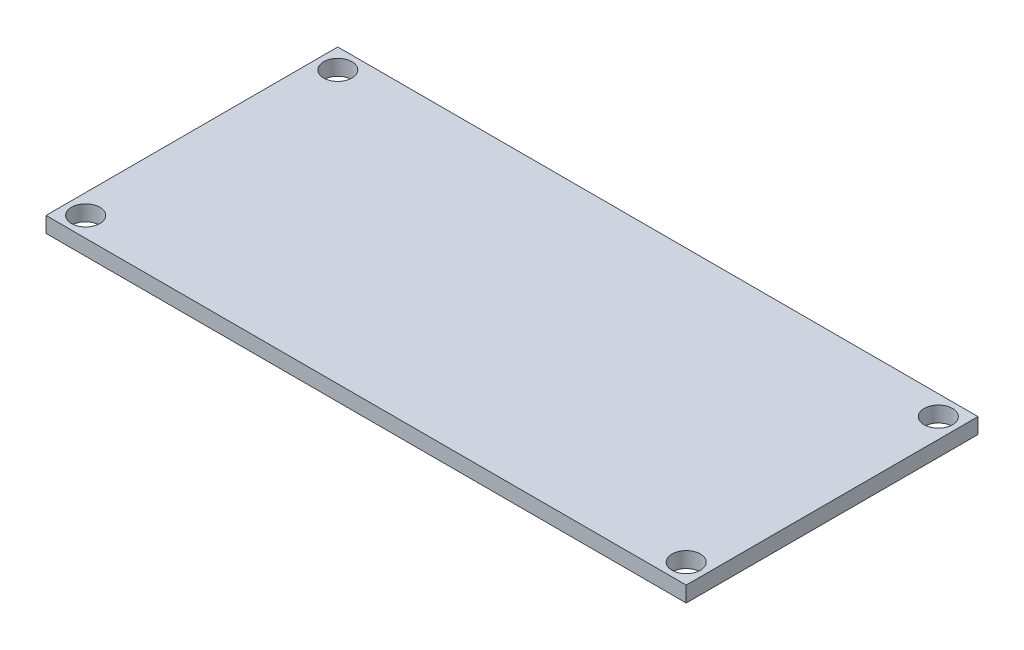
SolidWorks part; units mm, degrees
other "Camera2"
other "Camera3"
other "Camera5"
other "Camera6"
ref_plane "Front Plane" through (0, 0, 0) normal (0, 0, 1) x (1, 0, 0)
ref_plane "Top Plane" through (0, 0, 0) normal (0, 1, 0) x (1, 0, 0)
ref_plane "Right Plane" through (0, 0, 0) normal (1, 0, 0) x (0, 0, -1)
sketch "Sketch1" plane through (0, 0, 0) normal (0, 1, 0) x (1, 0, 0)
  line L1 (22.6, -10.3) -> (-22.6, -10.3)
  line L2 (22.6, -10.3) -> (22.6, 10.3)
  line L3 (22.6, 10.3) -> (-22.6, 10.3)
  line L4 (-22.6, -10.3) -> (-22.6, 10.3)
  line L5 (22.6, -10.3) -> (-22.6, 10.3) construction
  line L6 (22.6, 10.3) -> (-22.6, -10.3) construction
  point P0 (0, 0)
  dimension "D1" = 45.2
  dimension "D2" = 20.6
extrude "Boss-Extrude1" add sketch "Sketch1" along normal blind 1.1
sketch "Sketch18" plane through (0, 1.1, 0) normal (0, 1, 0) x (1, 0, 0)
  line L0 (22.6, 10.3) -> (-22.6, 10.3) construction
  line L2 (22.6, -10.3) -> (22.6, 10.3) construction
  line L4 (-22.6, -10.3) -> (22.6, -10.3) construction
  line L5 (-22.6, 10.3) -> (-22.6, -10.3) construction
  circle A0 centre (-21.2, -8.9) radius 1
  circle A1 centre (21.2, 8.9) radius 1
  point P3 (21.2, 9.9)
  point P4 (22.2, 8.9)
  point P16 (-22.2, -8.9)
  point P19 (-21.2, -9.9)
  dimension "D1" = 2
  dimension "D2" = 0.4
  dimension "D3" = 0.4
  dimension "D4" = 0.4
  dimension "D5" = 0.4
extrude "Cut-Extrude4" cut sketch "Sketch18" against normal through all
ref_plane "Plane3" [suppressed] through (0, -0.15, 0) normal (0, -1, 0) x (-1, 0, 0)
sketch "Sketch30" [suppressed] plane through (0, 0, 0) normal (0, -1, 0) x (1, 0, 0)
  circle A0 centre (-9.3331, 4.3877) radius 0.15
  circle A1 centre (-8.7445, 3.4491) radius 0.15
  circle A2 centre (4.7599, 5.0151) radius 0.15
  circle A3 centre (16.923, 5.2474) radius 0.15
  circle A4 centre (7.8306, -1.5279) radius 0.15
  circle A5 centre (7.8521, -0.5489) radius 0.15
  circle A6 centre (5.5498, -2.8081) radius 0.15
  circle A7 centre (5.8833, 1.6566) radius 0.15
  circle A8 centre (15.8275, -3.1155) radius 0.15
  circle A9 centre (21.3759, -3.9691) radius 0.15
  circle A10 centre (17.9615, -7.5844) radius 0.15
  circle A11 centre (15.356, -9.4499) radius 0.15
  circle A12 centre (3.5992, -6.1194) radius 0.15
  circle A13 centre (7.7403, -8.604) radius 0.15
  circle A14 centre (-0.5709, -8.7784) radius 0.15
  circle A15 centre (-2.9017, -4.6563) radius 0.15
  circle A16 centre (-4.1765, -4.6563) radius 0.15
  circle A17 centre (-5.4156, -1.349) radius 0.15
  circle A18 centre (-7.9014, -0.2789) radius 0.15
  circle A19 centre (-5.255, 5.1458) radius 0.15
  circle A20 centre (-3.8953, 7.0643) radius 0.15
  circle A21 centre (13.5745, 2.4948) radius 0.15
  circle A22 centre (10.0609, 0.5122) radius 0.15
  circle A23 centre (-12.8703, -7.2236) radius 0.15
  circle A24 centre (-20.0039, -5.4912) radius 0.15
  circle A25 centre (-22.3571, 3.2187) radius 0.15
  circle A26 centre (-22.3571, 1.9552) radius 0.15
  circle A27 centre (-22.3571, -1.9487) radius 0.15
  dimension "D1" = 0.3
extrude "Cut-Extrude6" [suppressed] cut sketch "Sketch30" against normal up to surface (1.1 mm away)
mirror "Mirror1" about plane through (0, 0, 0) normal (1, 0, 0) of "Cut-Extrude4"
